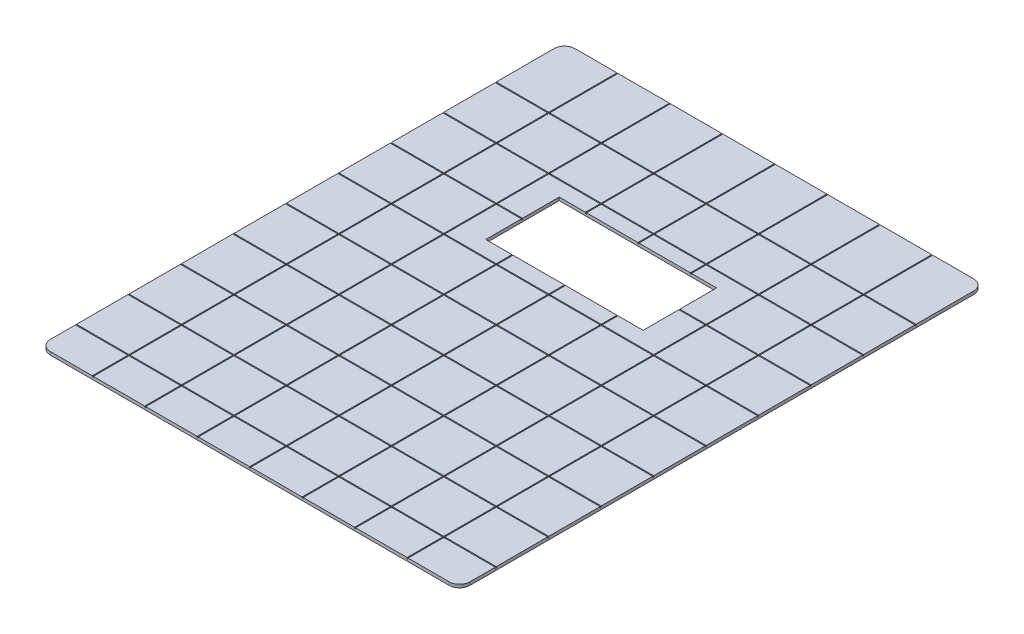
SolidWorks part; units mm, degrees
ref_plane "Front Plane" through (0, 0, 0) normal (0, 0, 1) x (1, 0, 0)
ref_plane "Top Plane" through (0, 0, 0) normal (0, 1, 0) x (1, 0, 0)
ref_plane "Right Plane" through (0, 0, 0) normal (1, 0, 0) x (0, 0, -1)
sketch "Sketch1" plane through (0, 0, 0) normal (0, 1, 0) x (1, 0, 0)
  line L1 (0, 0) -> (400, 0)
  line L2 (0, 0) -> (0, 500)
  line L3 (0, 500) -> (400, 500)
  line L4 (400, 0) -> (400, 500)
  dimension "D1" = 500
  dimension "D2" = 400
extrude "Boss-Extrude1" add sketch "Sketch1" along normal blind 3
sketch "Sketch2" plane through (0, 3, 0) normal (0, 1, 0) x (1, 0, 0)
  line L0 (400, 500) -> (0, 500) construction
  point P0 (200, 500)
fillet "Fillet1" radius 10 4 edges at (0, 1.5, -500) (400, 1.5, -500) (0, 1.5, 0) (400, 1.5, 0)
sketch "Sketch3" plane through (0, 3, 0) normal (0, 1, 0) x (1, 0, 0)
  line L0 (390, 500) -> (10, 500) construction
  line L1 (135, 360) -> (265, 360)
  line L2 (135, 360) -> (135, 310)
  line L3 (135, 310) -> (265, 310)
  line L4 (265, 360) -> (265, 310)
  line L5 (400, 10) -> (400, 490) construction
  line L6 (0, 490) -> (0, 10) construction
  line L7 (125, 370) -> (125, 300)
  line L8 (125, 300) -> (275, 300)
  line L9 (275, 370) -> (275, 300)
  line L10 (125, 370) -> (275, 370)
  dimension "D1" = 140
  dimension "D2" = 50
  dimension "D3" = 135
  dimension "D4" = 135
  dimension "D5" = 10
extrude "Cut-Extrude1" cut sketch "Sketch3" against normal blind 10 contours L4 L1 L2 L3 | L10 L7 L8 L9 L1 L4 L3 L2
sketch "Sketch5" plane through (0, 3, 0) normal (0, 1, 0) x (1, 0, 0)
  line L0 (125, 335) -> (275, 335) construction
  line L1 (125, 370) -> (125, 300) construction
  line L2 (275, 370) -> (275, 300) construction
  line L3 (200, 335) -> (200, 0) construction
  line L4 (0, 235) -> (400, 235)
  line L5 (0, 490) -> (0, 10) construction
  line L6 (400, 10) -> (400, 490) construction
  line L7 (0, 185) -> (400, 185)
  line L8 (0, 85) -> (400, 85)
  line L9 (0, 135) -> (400, 135)
  line L10 (0, 285) -> (400, 285)
  line L11 (0, 335) -> (400, 335)
  line L12 (0, 385) -> (400, 385)
  line L13 (0, 435) -> (400, 435)
  line L14 (0, 35) -> (400, 35)
  dimension "D1" = 250
  dimension "D2" = 100
  dimension "D3" = 150
  dimension "D4" = 200
  dimension "D5" = 50
  dimension "D6" = 50
  dimension "D7" = 50
  dimension "D8" = 100
  dimension "D9" = 50
extrude "Cut-Extrude-Thin1" cut sketch "Sketch5" against normal blind 1 thin
sketch "Sketch6" plane through (0, 3, 0) normal (0, 1, 0) x (1, 0, 0)
  line L0 (200, 500) -> (200, 0)
  line L1 (390, 500) -> (10, 500) construction
  line L2 (10, 0) -> (390, 0) construction
  line L3 (250, 500) -> (250, 0)
  line L4 (300, 500) -> (300, 0)
  line L5 (350, 500) -> (350, 0)
  line L6 (50, 500) -> (50, 0)
  line L7 (100, 500) -> (100, 0)
  line L8 (150, 500) -> (150, 0)
  point P12 (300, 0)
  point P13 (352.979, 0)
  dimension "D1" = 50
  dimension "D2" = 50
  dimension "D3" = 50
extrude "Cut-Extrude-Thin2" cut sketch "Sketch6" against normal blind 1 thin thin type one direction reverse wall 1
